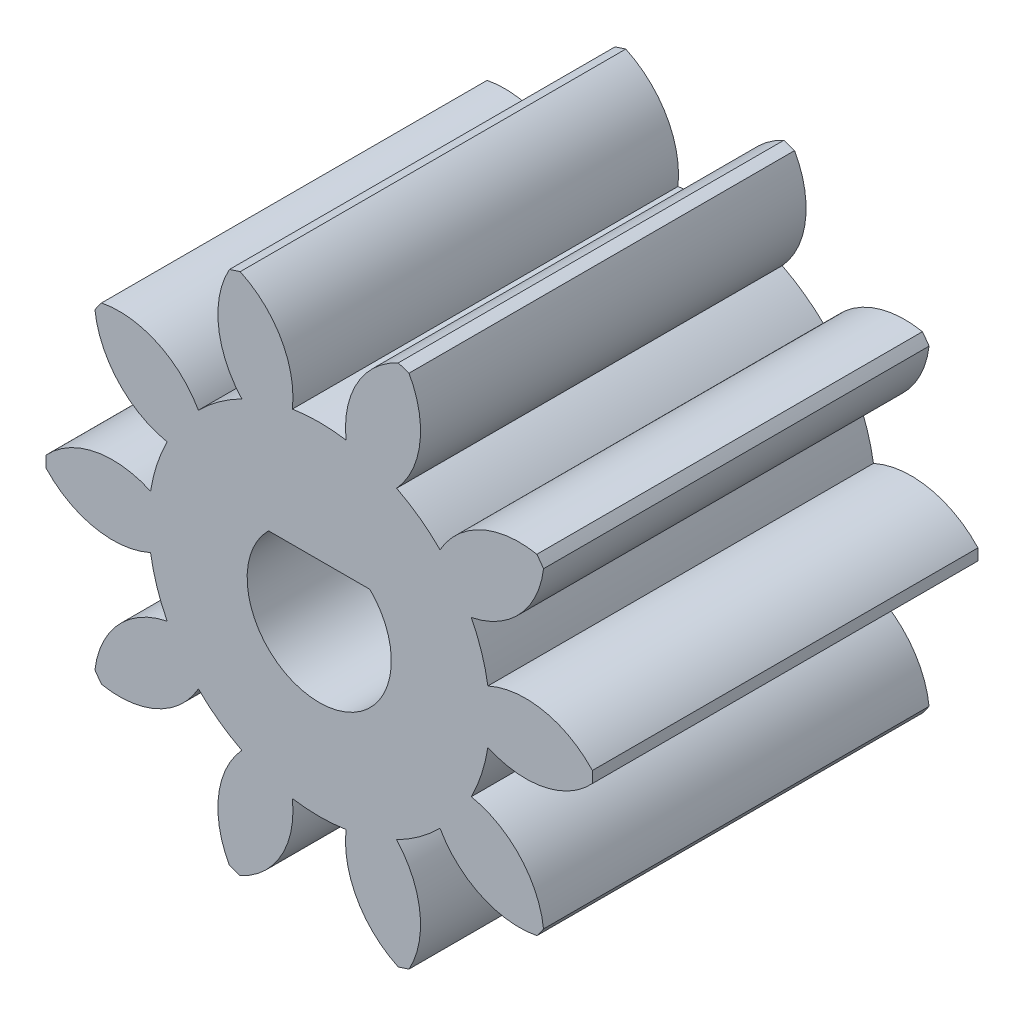
SolidWorks part; units mm, degrees
ref_plane "Front Plane" through (0, 0, 0) normal (0, 0, 1) x (1, 0, 0)
ref_plane "Top Plane" through (0, 0, 0) normal (0, 1, 0) x (1, 0, 0)
ref_plane "Right Plane" through (0, 0, 0) normal (1, 0, 0) x (0, 0, -1)
sketch "Sketch1" plane through (0, 0, 0) normal (0, 0, 1) x (1, 0, 0)
  arc A0 (-7.1698, 5.4401) -> (-7.3894, 5.1378) centre (0, 0) ccw
  arc A1 (-7.3894, 5.1378) -> (-5.0091, 2.5569) centre (-4.4109, 5.4967) ccw
  arc A2 (-5.0091, 2.5569) -> (-5.5554, 0.8757) centre (0, 0) ccw
  arc A3 (-5.5554, 0.8757) -> (-8.9981, 0.1868) centre (-6.7994, -1.8542) ccw
  arc A4 (-8.9981, 0.1868) -> (-8.9981, -0.1868) centre (0, 0) ccw
  arc A5 (-8.9981, -0.1868) -> (-5.5554, -0.8757) centre (-6.7994, 1.8542) ccw
  arc A6 (-5.5554, -0.8757) -> (-5.0091, -2.5569) centre (0, 0) ccw
  arc A7 (-5.0091, -2.5569) -> (-7.3894, -5.1378) centre (-4.4109, -5.4967) ccw
  arc A8 (-7.3894, -5.1378) -> (-7.1698, -5.4401) centre (0, 0) ccw
  arc A9 (-7.1698, -5.4401) -> (-3.9797, -3.9738) centre (-6.5907, -2.4965) ccw
  arc A10 (-3.9797, -3.9738) -> (-2.5496, -5.0129) centre (0, 0) ccw
  arc A11 (-2.5496, -5.0129) -> (-2.9582, -8.4999) centre (-0.3377, -7.0396) ccw
  arc A12 (-2.9582, -8.4999) -> (-2.6029, -8.6154) centre (0, 0) ccw
  arc A13 (-2.6029, -8.6154) -> (-0.8839, -5.5541) centre (-3.8646, -5.8936) ccw
  arc A14 (-0.8839, -5.5541) -> (0.8839, -5.5541) centre (0, 0) ccw
  arc A15 (0.8839, -5.5541) -> (2.6029, -8.6154) centre (3.8646, -5.8936) ccw
  arc A16 (2.6029, -8.6154) -> (2.9582, -8.4999) centre (0, 0) ccw
  arc A17 (2.9582, -8.4999) -> (2.5496, -5.0129) centre (0.3377, -7.0396) ccw
  arc A18 (2.5496, -5.0129) -> (3.9797, -3.9738) centre (0, 0) ccw
  arc A19 (3.9797, -3.9738) -> (7.1698, -5.4401) centre (6.5907, -2.4965) ccw
  arc A20 (7.1698, -5.4401) -> (7.3894, -5.1378) centre (0, 0) ccw
  arc A21 (7.3894, -5.1378) -> (5.0091, -2.5569) centre (4.4109, -5.4967) ccw
  arc A22 (5.0091, -2.5569) -> (5.5554, -0.8757) centre (0, 0) ccw
  arc A23 (5.5554, -0.8757) -> (8.9981, -0.1868) centre (6.7994, 1.8542) ccw
  arc A24 (8.9981, -0.1868) -> (8.9981, 0.1868) centre (0, 0) ccw
  arc A25 (8.9981, 0.1868) -> (5.5554, 0.8757) centre (6.7994, -1.8542) ccw
  arc A26 (5.5554, 0.8757) -> (5.0091, 2.5569) centre (0, 0) ccw
  arc A27 (5.0091, 2.5569) -> (7.3894, 5.1378) centre (4.4109, 5.4967) ccw
  arc A28 (7.3894, 5.1378) -> (7.1698, 5.4401) centre (0, 0) ccw
  arc A29 (7.1698, 5.4401) -> (3.9797, 3.9738) centre (6.5907, 2.4965) ccw
  arc A30 (3.9797, 3.9738) -> (2.5496, 5.0129) centre (0, 0) ccw
  arc A31 (2.5496, 5.0129) -> (2.9582, 8.4999) centre (0.3377, 7.0396) ccw
  arc A32 (2.9582, 8.4999) -> (2.6029, 8.6154) centre (0, 0) ccw
  arc A33 (2.6029, 8.6154) -> (0.8839, 5.5541) centre (3.8646, 5.8936) ccw
  arc A34 (0.8839, 5.5541) -> (-0.8839, 5.5541) centre (0, 0) ccw
  arc A35 (-0.8839, 5.5541) -> (-2.6029, 8.6154) centre (-3.8646, 5.8936) ccw
  arc A36 (-2.6029, 8.6154) -> (-2.9582, 8.4999) centre (0, 0) ccw
  arc A37 (-2.9582, 8.4999) -> (-2.5496, 5.0129) centre (-0.3377, 7.0396) ccw
  arc A38 (-2.5496, 5.0129) -> (-3.9797, 3.9738) centre (0, 0) ccw
  arc A39 (-3.9797, 3.9738) -> (-7.1698, 5.4401) centre (-6.5907, 2.4965) ccw
extrude "Boss-Extrude1" add sketch "Sketch1" along normal blind 12.7
sketch "Sketch2" plane through (0, 0, 12.7) normal (0, 0, 1) x (1, 0, 0)
  line L0 (1.6695, 1.6891) -> (-1.6695, 1.6891)
  arc A0 (-1.6695, 1.6891) -> (1.6695, 1.6891) centre (0, 0) ccw
  arc A1 (5.0091, -2.5569) -> (5.5554, -0.8757) centre (0, 0) ccw construction
  dimension "D2" = 2.3749
  dimension "D1" = 3.3389
extrude "Cut-Extrude1" cut sketch "Sketch2" against normal up to next
